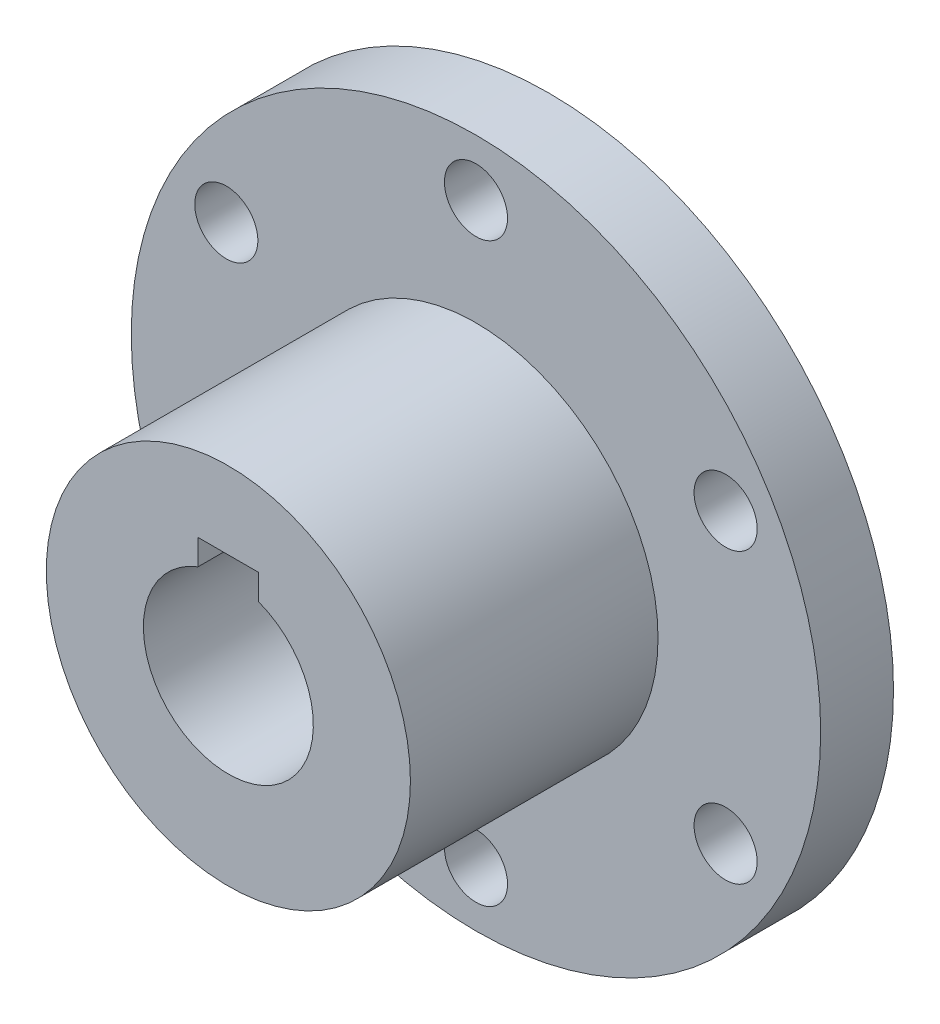
SolidWorks part; units mm, degrees
ref_plane "前视基准面" through (0, 0, 0) normal (0, 0, 1) x (1, 0, 0)
ref_plane "上视基准面" through (0, 0, 0) normal (0, 1, 0) x (1, 0, 0)
ref_plane "右视基准面" through (0, 0, 0) normal (1, 0, 0) x (0, 0, -1)
sketch "草图1" plane through (0, 0, 0) normal (0, 0, 1) x (1, 0, 0)
  circle A0 centre (0, 8.733) radius 28.4
  dimension "D1" = 56.8
extrude "凸台-拉伸1" add sketch "草图1" along normal blind 6
sketch "草图2" plane through (0, 0, 6) normal (0, 0, 1) x (1, 0, 0)
  line L0 (0, 37.133) -> (0, -19.667) construction
  circle A0 centre (0, 8.733) radius 28.4 construction
  circle A1 centre (0, 8.733) radius 15
  dimension "D1" = 30
extrude "凸台-拉伸2" add sketch "草图2" along normal blind 20.4
sketch "草图3" plane through (0, 0, 26.4) normal (0, 0, 1) x (1, 0, 0)
  line L0 (0, 23.733) -> (0, -6.267) construction
  circle A0 centre (0, 8.733) radius 15 construction
  circle A1 centre (0, 8.733) radius 15 construction
  circle A2 centre (0, 8.733) radius 7
  dimension "D1" = 14
extrude "切除-拉伸1" cut sketch "草图3" against normal through all
sketch "草图4" plane through (0, 0, 26.4) normal (0, 0, 1) x (1, 0, 0)
  line L0 (0, 15.733) -> (0, 1.733) construction
  line L1 (-2.5, 17.3714) -> (2.5, 17.3714)
  line L2 (2.5, 17.3714) -> (2.5, 15.2714)
  line L3 (2.5, 15.2714) -> (-2.5, 15.2714)
  line L4 (-2.5, 15.2714) -> (-2.5, 17.3714)
  circle A1 centre (0, 8.733) radius 7 construction
  point P6 (0, 17.3714)
  dimension "D1" = 5
  dimension "D2" = 2.1
extrude "切除-拉伸2" cut sketch "草图4" against normal through all
sketch "草图5" plane through (0, 0, 6) normal (0, 0, 1) x (1, 0, 0)
  line L0 (0, 37.133) -> (0, -19.667) construction
  circle A0 centre (0, 8.733) radius 28.4 construction
  circle A1 centre (0, 32.483) radius 2.6
  circle A2 centre (20.5681, 20.608) radius 2.6
  circle A3 centre (20.5681, -3.142) radius 2.6
  circle A4 centre (0, -15.017) radius 2.6
  circle A5 centre (-20.5681, -3.142) radius 2.6
  circle A6 centre (-20.5681, 20.608) radius 2.6
  point P9 (0, 8.733)
  point P20 (0, 8.733)
  dimension "D1" = 5.2
  dimension "D2" = 23.75
  dimension "D3" = 6
extrude "切除-拉伸3" cut sketch "草图5" against normal through all
